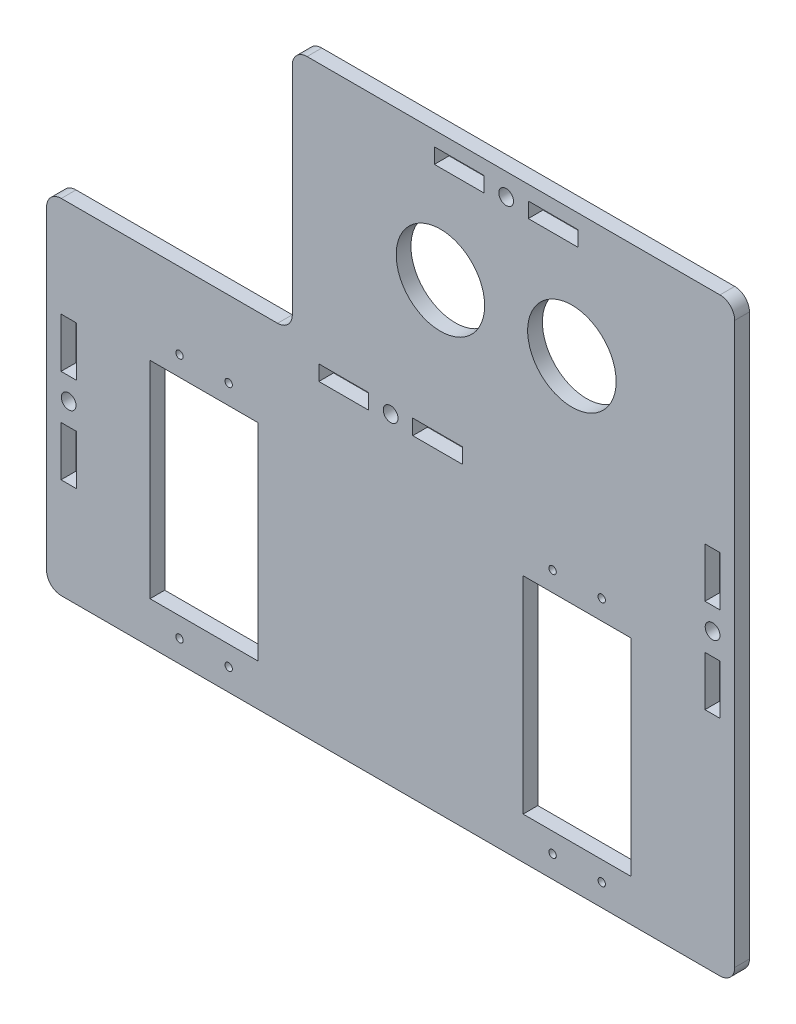
SolidWorks part; units mm, degrees
ref_plane "Front Plane" through (0, 0, 0) normal (0, 0, 1) x (1, 0, 0)
ref_plane "Top Plane" through (0, 0, 0) normal (0, 1, 0) x (1, 0, 0)
ref_plane "Right Plane" through (0, 0, 0) normal (1, 0, 0) x (0, 0, -1)
sketch "Sketch1" plane through (0, 0, 0) normal (0, 0, 1) x (1, 0, 0)
  line L0 (4.5, 120) -> (4.5, 0) construction
  line L1 (0, 0) -> (140, 0)
  line L2 (0, 0) -> (0, 120)
  line L3 (0, 120) -> (140, 120)
  line L4 (140, 0) -> (140, 120)
  line L5 (0, 4.5) -> (140, 4.5) construction
  line L6 (140, 115.5) -> (0, 115.5) construction
  line L7 (135.5, 120) -> (135.5, 0) construction
  line L8 (140, 60) -> (0, 60) construction
  line L9 (70, 120) -> (70, 0) construction
  line L10 (133.95, 45.4) -> (137.05, 45.4)
  line L11 (133.95, 74.6) -> (137.05, 74.6)
  line L12 (133.95, 74.6) -> (133.95, 64.5)
  line L13 (133.95, 64.5) -> (137.05, 64.5)
  line L14 (137.05, 74.6) -> (137.05, 64.5)
  line L15 (133.95, 45.4) -> (133.95, 55.5)
  line L16 (133.95, 55.5) -> (137.05, 55.5)
  line L17 (137.05, 45.4) -> (137.05, 55.5)
  line L18 (0, 35) -> (140, 35) construction
  line L19 (2.95, 20.4) -> (6.05, 20.4)
  line L20 (2.95, 49.6) -> (6.05, 49.6)
  line L21 (2.95, 49.6) -> (2.95, 39.5)
  line L22 (2.95, 39.5) -> (6.05, 39.5)
  line L23 (6.05, 49.6) -> (6.05, 39.5)
  line L24 (2.95, 20.4) -> (2.95, 30.5)
  line L25 (2.95, 30.5) -> (6.05, 30.5)
  line L26 (6.05, 20.4) -> (6.05, 30.5)
  line L27 (65.5, 67.05) -> (65.5, 63.95)
  line L28 (74.5, 67.05) -> (84.6, 67.05)
  line L29 (74.5, 67.05) -> (74.5, 63.95)
  line L30 (74.5, 63.95) -> (84.6, 63.95)
  line L31 (84.6, 67.05) -> (84.6, 63.95)
  line L32 (65.5, 67.05) -> (55.4, 67.05)
  line L33 (55.4, 67.05) -> (55.4, 63.95)
  line L34 (65.5, 63.95) -> (55.4, 63.95)
  line L35 (102.95, 54.5) -> (112.95, 54.5) construction
  line L36 (102.95, 4.5) -> (112.95, 4.5) construction
  line L37 (107.95, 54.5) -> (107.95, 4.5) construction
  line L38 (96.95, 29.5) -> (118.95, 29.5) construction
  line L39 (112.95, 54.5) -> (112.95, 4.5) construction
  line L40 (102.95, 54.5) -> (102.95, 4.5) construction
  line L41 (43.05, 50.5) -> (43.05, 8.5)
  line L42 (43.05, 8.5) -> (21.05, 8.5)
  line L43 (21.05, 50.5) -> (21.05, 8.5)
  line L44 (43.05, 50.5) -> (21.05, 50.5)
  line L45 (96.95, 50.5) -> (96.95, 8.5)
  line L46 (96.95, 50.5) -> (118.95, 50.5)
  line L47 (118.95, 50.5) -> (118.95, 8.5)
  line L48 (96.95, 8.5) -> (118.95, 8.5)
  line L49 (55.5, 65.5) -> (84.6, 65.5) construction
  line L50 (0, 70) -> (50, 70)
  line L51 (0, 70) -> (0, 120)
  line L52 (0, 120) -> (50, 120)
  line L53 (50, 70) -> (50, 120)
  line L54 (80.1282, 94.16) -> (106.8782, 94.16) construction
  line L55 (93.5032, 94.16) -> (93.5032, 120) construction
  line L56 (108.1032, 117.05) -> (108.1032, 113.95)
  line L57 (78.9032, 117.05) -> (89.0032, 117.05)
  line L58 (78.9032, 117.05) -> (78.9032, 113.95)
  line L59 (78.9032, 113.95) -> (89.0032, 113.95)
  line L60 (89.0032, 117.05) -> (89.0032, 113.95)
  line L61 (108.1032, 113.95) -> (98.0032, 113.95)
  line L62 (98.0032, 117.05) -> (98.0032, 113.95)
  line L63 (108.1032, 117.05) -> (98.0032, 117.05)
  circle A0 centre (135.5, 60) radius 1.5
  circle A1 centre (4.5, 35) radius 1.5
  circle A2 centre (70, 65.5) radius 1.5
  circle A3 centre (27.05, 4.5) radius 0.75
  circle A4 centre (37.05, 4.5) radius 0.75
  circle A5 centre (37.05, 54.5) radius 0.75
  circle A6 centre (27.05, 54.5) radius 0.75
  circle A7 centre (102.95, 54.5) radius 0.75
  circle A8 centre (112.95, 54.5) radius 0.75
  circle A9 centre (102.95, 4.5) radius 0.75
  circle A10 centre (112.95, 4.5) radius 0.75
  circle A11 centre (80.1282, 94.16) radius 9
  circle A12 centre (106.8782, 94.16) radius 9
  circle A13 centre (93.5032, 115.5) radius 1.5
  point P23 (135.5, 74.6)
  point P36 (4.5, 49.6)
  point P56 (107.95, 29.5)
  point P87 (84.6, 65.5)
  point P98 (89.0032, 115.5)
  dimension "D7" = 3
  dimension "D12" = 3
  dimension "D16" = 3
  dimension "D23" = 10
  dimension "D24" = 1.5
  dimension "D30" = 18
  dimension "D25" = 25.84
  dimension "D32" = 3
  dimension "D1" = 140
  dimension "D2" = 120
  dimension "D3" = 4.5
  dimension "D4" = 4.5
  dimension "D5" = 4.5
  dimension "D6" = 4.5
  dimension "D8" = 3.1
  dimension "D9" = 10.1
  dimension "D10" = 4.5
  dimension "D11" = 35
  dimension "D13" = 3.1
  dimension "D14" = 10.1
  dimension "D15" = 4.5
  dimension "D17" = 10.1
  dimension "D18" = 3.1
  dimension "D19" = 4.5
  dimension "D20" = 42
  dimension "D21" = 50
  dimension "D22" = 22
  dimension "D26" = 26.75
  dimension "D27" = 50
  dimension "D28" = 50
  dimension "D29" = 4.5
  dimension "10" = 15
  dimension "D31" = 92.9936
  dimension "D33" = 3.1
  dimension "D34" = 10.1
  dimension "D35" = 4.5
extrude "Boss-Extrude4" add sketch "Sketch1" along normal blind 3
fillet "Fillet1" radius 3 6 edges at (140, 120, 1.5) (140, 0, 1.5) (0, 0, 1.5) (0, 70, 1.5) (50, 120, 1.5) (50, 70, 1.5)
equation "\"D4@Sketch1\"=\"D3@Sketch1\""
equation "\"D6@Sketch1\"=\"D3@Sketch1\""
equation "\"D5@Sketch1\"=\"D3@Sketch1\""
equation "\"D11@Sketch1\"=(\"D2@Sketch1\" - \"D28@Sketch1\")/2"
equation "\"D12@Sketch1\"=\"D7@Sketch1\""
equation "\"D13@Sketch1\"=\"D8@Sketch1\""
equation "\"D14@Sketch1\"=\"D9@Sketch1\""
equation "\"D15@Sketch1\"=\"D10@Sketch1\""
equation "\"D16@Sketch1\"=\"D7@Sketch1\""
equation "\"D17@Sketch1\"=\"D9@Sketch1\""
equation "\"D18@Sketch1\"=\"D8@Sketch1\""
equation "\"D19@Sketch1\"=\"D10@Sketch1\""
equation "\"D29@Sketch1\"=\"D4@Sketch1\""
equation "\"D26@Sketch1\"=(42.75 - 16)"
equation "\"D32@Sketch1\"=\"D7@Sketch1\""
equation "\"D34@Sketch1\"=\"D9@Sketch1\""
equation "\"D35@Sketch1\"=\"D10@Sketch1\""
equation "\"D33@Sketch1\"=\"D8@Sketch1\""
